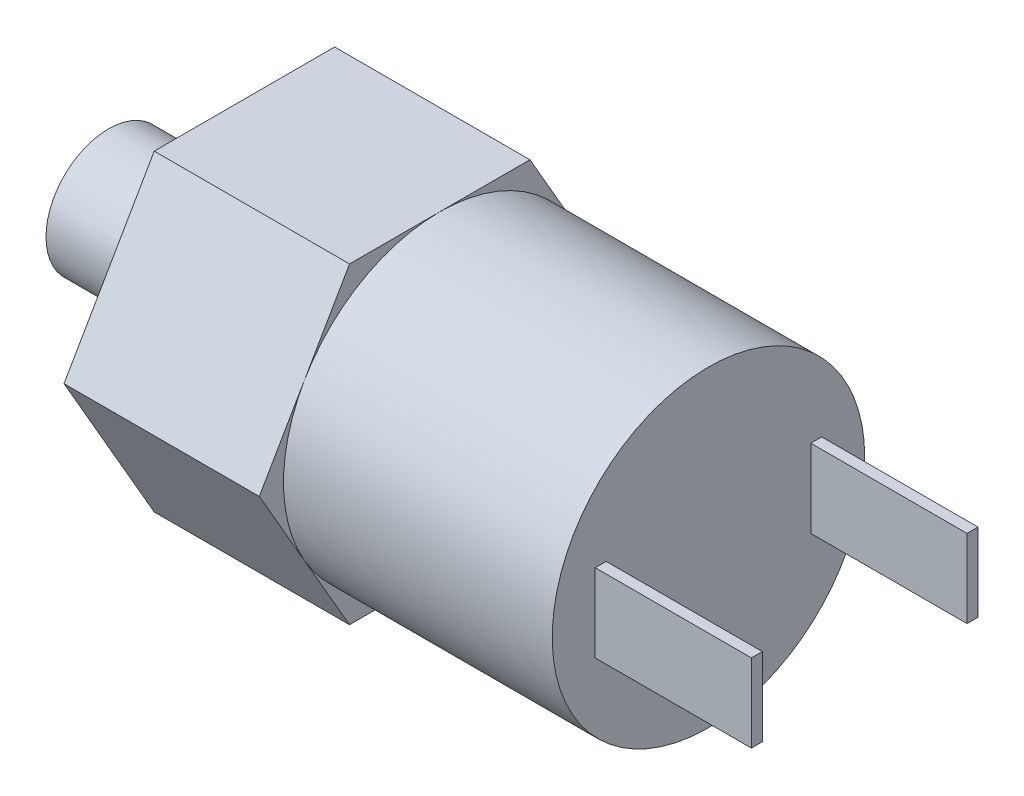
SolidWorks part; units mm, degrees
material "6061-T6 (SS)"
ref_plane "Front Plane" through (0, 0, 0) normal (0, 0, 1) x (1, 0, 0)
ref_plane "Top Plane" through (0, 0, 0) normal (0, 1, 0) x (1, 0, 0)
ref_plane "Right Plane" through (0, 0, 0) normal (1, 0, 0) x (0, 0, -1)
sketch "Sketch1" plane through (0, 0, 0) normal (1, 0, 0) x (0, 0, -1)
  line L1 (14.6647, 0) -> (7.3323, 12.7)
  line L2 (7.3323, 12.7) -> (-7.3323, 12.7)
  line L3 (-7.3323, 12.7) -> (-14.6647, 0)
  line L4 (-14.6647, 0) -> (-7.3323, -12.7)
  line L5 (-7.3323, -12.7) -> (7.3323, -12.7)
  line L6 (7.3323, -12.7) -> (14.6647, 0)
  circle A0 centre (0, 0) radius 12.7 construction
  dimension "D1" = 25.4
extrude "Boss-Extrude1" add sketch "Sketch1" along normal blind 15.875
sketch "Sketch2" plane through (15.875, 0, 0) normal (1, 0, 0) x (0, 0, -1)
  circle A0 centre (0, 0) radius 12.7
  dimension "D1" = 25.4
extrude "Boss-Extrude2" add sketch "Sketch2" along normal blind 21.844
sketch "Sketch3" plane through (0, 0, 0) normal (-1, 0, 0) x (0, 0, 1)
  circle A0 centre (0, 0) radius 5.08
  dimension "D1" = 10.16
extrude "Boss-Extrude3" add sketch "Sketch3" along normal blind 11.049
fillet "Fillet1" radius 1.905 1 edges at (0, 0, -5.08)
sketch "Sketch4" plane through (37.719, 0, 0) normal (1, 0, 0) x (0, 0, -1)
  line L0 (0, 0) -> (8.763, 0) construction
  line L1 (-8.3185, -3.175) -> (-9.2075, -3.175)
  line L2 (8.3185, 3.175) -> (9.2075, 3.175)
  line L3 (8.3185, 3.175) -> (8.3185, -3.175)
  line L4 (8.3185, -3.175) -> (9.2075, -3.175)
  line L5 (9.2075, 3.175) -> (9.2075, -3.175)
  line L6 (8.3185, 3.175) -> (9.2075, -3.175) construction
  line L7 (8.3185, -3.175) -> (9.2075, 3.175) construction
  line L8 (-8.3185, -3.175) -> (-8.3185, 3.175)
  line L9 (-8.3185, 3.175) -> (-9.2075, 3.175)
  line L10 (-9.2075, -3.175) -> (-9.2075, 3.175)
  line L11 (-8.3185, -3.175) -> (-9.2075, 3.175) construction
  line L12 (-8.3185, 3.175) -> (-9.2075, -3.175) construction
  point P14 (0, 0)
  dimension "D1" = 6.35
  dimension "D2" = 0.889
  dimension "D3" = 9.2075
  dimension "D4" = 2
extrude "Boss-Extrude4" add sketch "Sketch4" along normal blind 12.7
